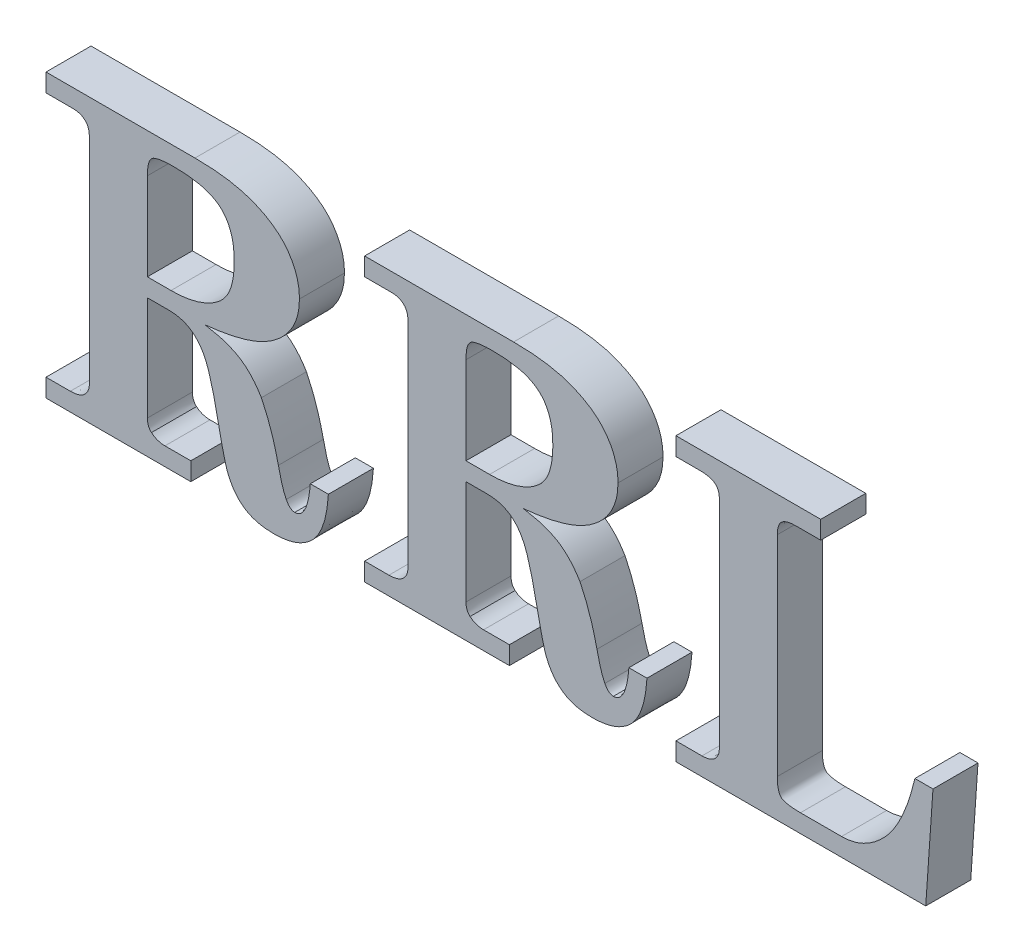
SolidWorks part; units mm, degrees
ref_plane "Front Plane" through (0, 0, 0) normal (0, 0, 1) x (1, 0, 0)
ref_plane "Top Plane" through (0, 0, 0) normal (0, 1, 0) x (1, 0, 0)
ref_plane "Right Plane" through (0, 0, 0) normal (1, 0, 0) x (0, 0, -1)
sketch "Sketch1" plane through (0, 0, 0) normal (0, 0, 1) x (1, 0, 0)
  line L0 (180, 540) -> (900, 540) construction
  text T0 "RRL" font "Century Schoolbook" height in points 36
extrude "Boss-Extrude3" add sketch "Sketch1" along normal blind 1.5
